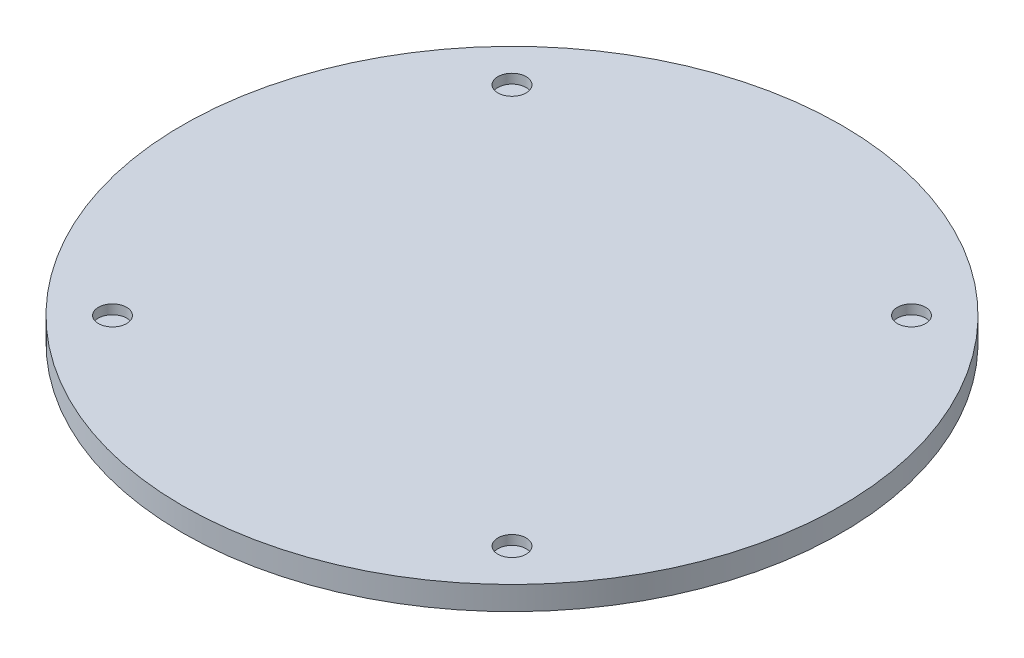
SolidWorks part; units mm, degrees
ref_plane "前视基准面" through (0, 0, 0) normal (0, 0, 1) x (1, 0, 0)
ref_plane "上视基准面" through (0, 0, 0) normal (0, 1, 0) x (1, 0, 0)
ref_plane "右视基准面" through (0, 0, 0) normal (1, 0, 0) x (0, 0, -1)
sketch "草图1" plane through (0, 0, 0) normal (0, 1, 0) x (1, 0, 0)
  circle A0 centre (0, 0) radius 70
  dimension "D1" = 140
extrude "凸台-拉伸1" add sketch "草图1" along normal blind 5
sketch "草图2" plane through (0, 5, 0) normal (0, 1, 0) x (1, 0, 0)
  line L1 (-42.4264, 42.4264) -> (42.4264, 42.4264) construction
  line L2 (-42.4264, 42.4264) -> (-42.4264, -42.4264) construction
  line L3 (-42.4264, -42.4264) -> (42.4264, -42.4264) construction
  line L4 (42.4264, 42.4264) -> (42.4264, -42.4264) construction
  line L5 (-42.4264, 42.4264) -> (42.4264, -42.4264) construction
  line L6 (-42.4264, -42.4264) -> (42.4264, 42.4264) construction
  circle A0 centre (-42.4264, 42.4264) radius 3
  circle A1 centre (42.4264, 42.4264) radius 3
  circle A2 centre (-42.4264, -42.4264) radius 3
  circle A3 centre (42.4264, -42.4264) radius 3
  point P0 (0, 0)
  dimension "D2" = 6
  dimension "D1" = 120
extrude "切除-拉伸1" cut sketch "草图2" against normal blind 2
